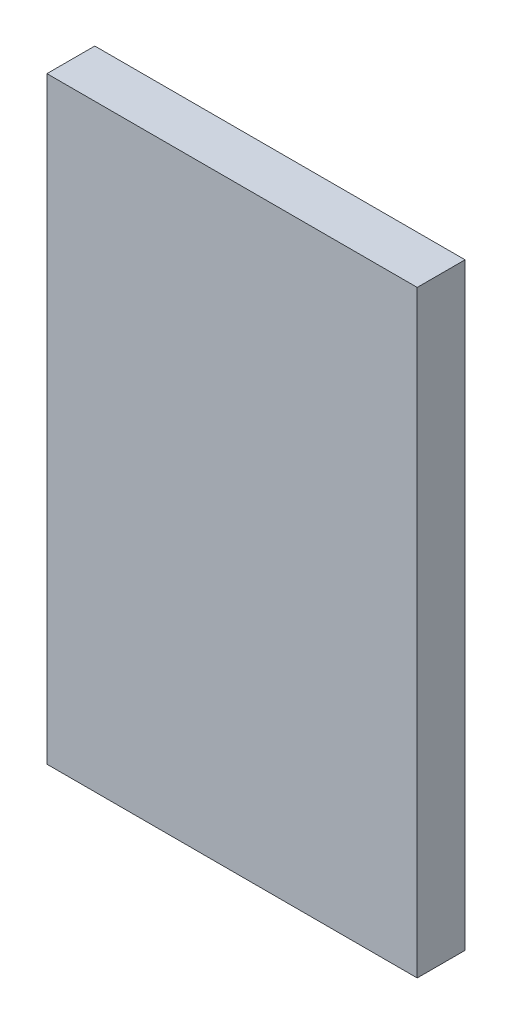
SolidWorks part; units mm, degrees
ref_plane "前视基准面" through (0, 0, 0) normal (0, 0, 1) x (1, 0, 0)
ref_plane "上视基准面" through (0, 0, 0) normal (0, 1, 0) x (1, 0, 0)
ref_plane "右视基准面" through (0, 0, 0) normal (1, 0, 0) x (0, 0, -1)
other "Configuration Table"
sketch "草图1" plane through (0, 0, 0) normal (0, 0, 1) x (1, 0, 0)
  line L8 (-5.678, 3.45) -> (9.8, 3.45)
  line L9 (9.8, 3.45) -> (9.8, 28.45)
  line L10 (9.8, 28.45) -> (-5.678, 28.45)
  line L11 (-5.678, 28.45) -> (-5.678, 3.45)
extrude "凸台-拉伸1" add sketch "草图1" along normal blind 2
